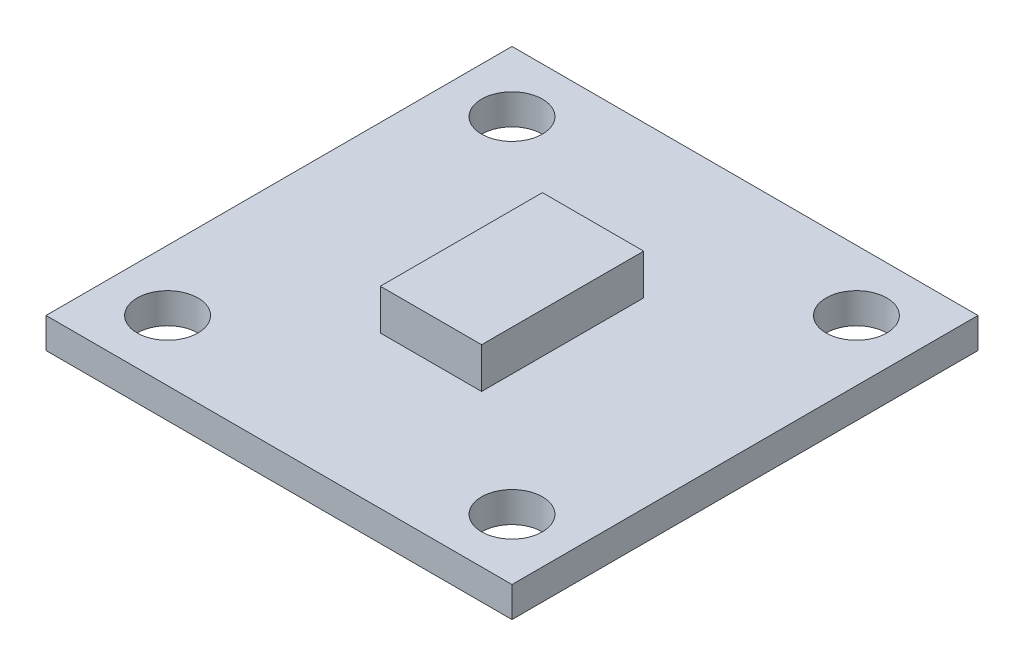
SolidWorks part; units mm, degrees
ref_plane "前视基准面" through (0, 0, 0) normal (0, 0, 1) x (1, 0, 0)
ref_plane "上视基准面" through (0, 0, 0) normal (0, 1, 0) x (1, 0, 0)
ref_plane "右视基准面" through (0, 0, 0) normal (1, 0, 0) x (0, 0, -1)
sketch "草图1" plane through (0, 0, 0) normal (0, 1, 0) x (1, 0, 0)
  line L0 (0, -11.3606) -> (0, 24.8462) construction
  line L1 (-21.7404, 0) -> (31.0577, 0) construction
  line L2 (-11.5, 11.5) -> (11.5, 11.5)
  line L3 (11.5, 11.5) -> (11.5, -11.5)
  line L4 (-11.5, -11.5) -> (11.5, -11.5)
  line L5 (-11.5, 11.5) -> (-11.5, -11.5)
  circle A0 centre (8.5, 8.5) radius 1.5
  circle A1 centre (8.5, -8.5) radius 1.5
  circle A2 centre (-8.5, -8.5) radius 1.5
  circle A3 centre (-8.5, 8.5) radius 1.5
  point P5 (-11.5, 0)
  point P11 (11.5, 0)
  point P19 (0, -11.5)
  point P20 (0, 11.5)
  dimension "D1" = 17
  dimension "D2" = 17
  dimension "D5" = 3
  dimension "D3" = 23
  dimension "D4" = 23
extrude "凸台-拉伸1" add sketch "草图1" along normal blind 1.5
sketch "草图2" plane through (0, 1.5, 0) normal (0, 1, 0) x (1, 0, 0)
  line L0 (0, 0) -> (0, 12.2698) construction
  line L1 (0, 0) -> (14.0623, 0) construction
  line L2 (-2.5, 4) -> (2.5, 4)
  line L3 (2.5, 4) -> (2.5, -4)
  line L4 (-2.5, -4) -> (2.5, -4)
  line L5 (-2.5, 4) -> (-2.5, -4)
  point P4 (-2.5, 0)
  point P8 (2.5, 0)
  point P10 (0, -4)
  point P11 (0, 4)
  dimension "D1" = 5
  dimension "D2" = 8
extrude "凸台-拉伸2" add sketch "草图2" along normal blind 2
